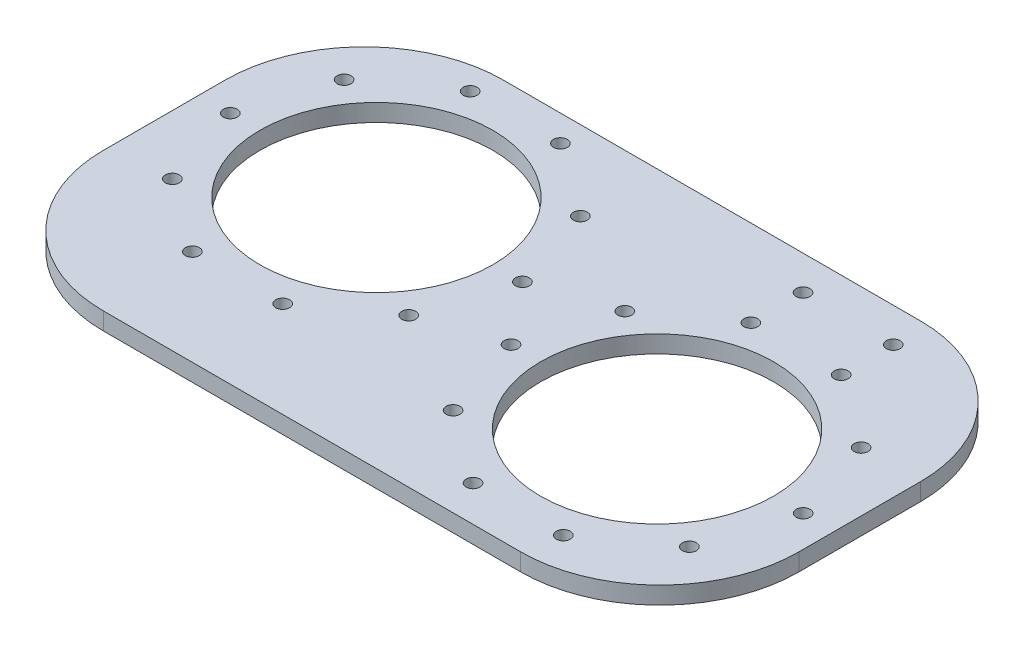
SolidWorks part; units mm, degrees
ref_plane "前基準面" through (0, 0, 0) normal (0, 0, 1) x (1, 0, 0)
ref_plane "上基準面" through (0, 0, 0) normal (0, 1, 0) x (1, 0, 0)
ref_plane "右基準面" through (0, 0, 0) normal (1, 0, 0) x (0, 0, -1)
sketch "草圖1" plane through (0, 0, 0) normal (0, 1, 0) x (1, 0, 0)
  line L0 (49, -7.28) -> (-49, 10) construction
  line L1 (-60, 57.5) -> (60, 57.5)
  line L2 (-100, 17.5) -> (-100, -17.5)
  line L3 (-60, -57.5) -> (60, -57.5)
  line L4 (100, 17.5) -> (100, -17.5)
  line L5 (-100, 57.5) -> (100, -57.5) construction
  line L6 (-100, -57.5) -> (100, 57.5) construction
  line L7 (-49, 10) -> (49, 10) construction
  arc A0 (-100, 17.5) -> (-60, 57.5) centre (-60, 17.5) cw
  arc A1 (60, -57.5) -> (100, -17.5) centre (60, -17.5) ccw
  arc A2 (-60, -57.5) -> (-100, -17.5) centre (-60, -17.5) cw
  arc A3 (100, 17.5) -> (60, 57.5) centre (60, 17.5) ccw
  circle A4 centre (-49, 10) radius 33.5
  circle A5 centre (49, -7.28) radius 33.5
  point P0 (0, 0)
  point P24 (0, 57.5)
  point P25 (0, 10)
  dimension "D2" = 40
  dimension "D5" = 67
  dimension "D6" = 10
  dimension "D3" = 200
  dimension "D4" = 115
  dimension "D7" = 10
  dimension "D8" = 98
extrude "填料-伸長1" add sketch "草圖1" along normal blind 5
sketch "草圖2" plane through (0, 5, 0) normal (0, 1, 0) x (1, 0, 0)
  circle A0 centre (49, -7.28) radius 42 construction
  circle A1 centre (91, -7.28) radius 2
  dimension "D1" = 84
  dimension "D2" = 4
extrude "除料-伸長1" cut sketch "草圖2" against normal up to next
pattern_circular "環狀複製排列1" count 10 over 360 about axis through (49, 0, 7.28) along (0, 1, 0) of "除料-伸長1"
sketch "草圖3" plane through (0, 5, 0) normal (0, 1, 0) x (1, 0, 0)
  circle A0 centre (-49, 10) radius 42 construction
  circle A1 centre (-7, 10) radius 2
  circle A2 centre (15.0213, 17.4069) radius 2 construction
  dimension "D1" = 84
extrude "除料-伸長2" cut sketch "草圖3" against normal up to next
pattern_circular "環狀複製排列2" count 10 over 360 about axis through (-49, 0, -10) along (0, 1, 0) of "除料-伸長2"
sketch "草圖4" plane through (0, 5, 0) normal (0, 1, 0) x (1, 0, 0)
  circle A2 centre (61.9787, 32.6643) radius 2 construction
  circle A3 centre (36.0213, 47.6643) radius 2
  circle A4 centre (61.9787, 47.6643) radius 2
  point P4 (36.0213, 32.6643)
  point P7 (61.9787, 32.6643)
  dimension "D1" = 15
extrude "除料-伸長3" cut sketch "草圖4" against normal up to next
